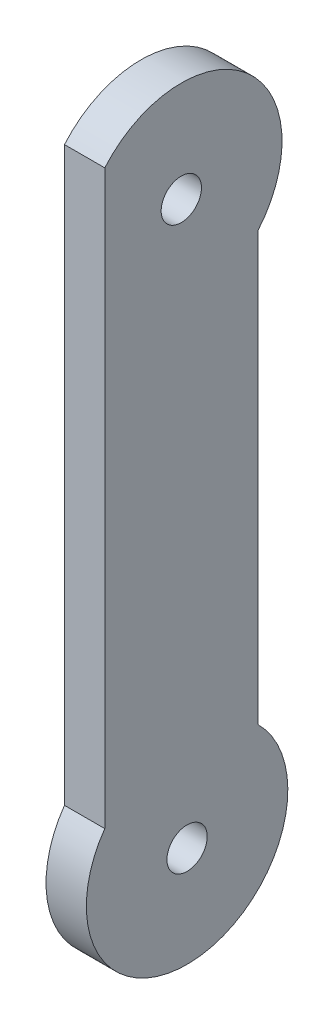
SolidWorks part; units mm, degrees
ref_plane "Front Plane" through (0, 0, 0) normal (0, 0, 1) x (1, 0, 0)
ref_plane "Top Plane" through (0, 0, 0) normal (0, 1, 0) x (1, 0, 0)
ref_plane "Right Plane" through (0, 0, 0) normal (1, 0, 0) x (0, 0, -1)
sketch "Sketch1" plane through (0, 0, 0) normal (1, 0, 0) x (0, 0, -1)
  line L2 (-21.7404, 79.3348) -> (-21.7404, -62.6652)
  line L4 (16.2429, 46.819) -> (16.2429, -59.2733)
  line L5 (-21.7404, 79.3348) -> (16.2429, -59.2733) construction
  line L6 (-21.7404, -62.6652) -> (16.2429, 46.819) construction
  arc A0 (-21.7404, 79.3348) -> (16.2429, 46.819) centre (-2.7488, 63.0769) cw
  arc A1 (-21.7404, -62.6652) -> (16.2429, -59.2733) centre (-1.3106, -77.0744) ccw
  point P0 (0, 0)
  dimension "D1" = 50
  dimension "D2" = 142
extrude "Boss-Extrude1" add sketch "Sketch1" along normal blind 10
sketch "Sketch2" plane through (10, 0, 0) normal (1, 0, 0) x (0, 0, -1)
  circle A0 centre (-2.7488, 63.0769) radius 5
  circle A1 centre (-1.3106, -77.0744) radius 5
  dimension "D1" = 10
  dimension "D2" = 10
extrude "Cut-Extrude1" cut sketch "Sketch2" against normal blind 10
